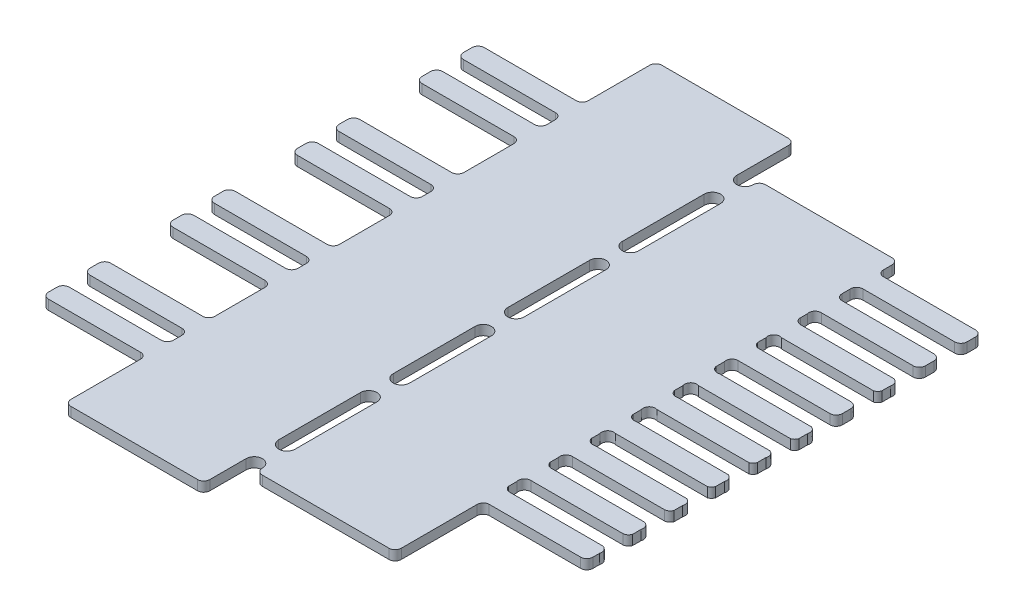
SolidWorks part; units mm, degrees
ref_plane "Front Plane" through (0, 0, 0) normal (0, 0, 1) x (1, 0, 0)
ref_plane "Top Plane" through (0, 0, 0) normal (0, 1, 0) x (1, 0, 0)
ref_plane "Right Plane" through (0, 0, 0) normal (1, 0, 0) x (0, 0, -1)
sketch "Sketch1" plane through (0, 0, 0) normal (0, 1, 0) x (1, 0, 0)
  line L0 (-0.75, 10) -> (-12, 10)
  line L2 (0, 9.25) -> (0, 0.75)
  line L5 (-12.75, 11.27) -> (0, 11.27) construction
  line L7 (-12.75, 10.75) -> (-12.75, 11.79)
  line L8 (-12, 12.54) -> (-0.75, 12.54)
  line L12 (0, 14.33) -> (0, 13.29)
  line L17 (-0.75, 15.08) -> (-12, 15.08)
  line L22 (-12.75, 15.83) -> (-12.75, 16.87)
  line L27 (-12, 17.62) -> (-0.75, 17.62)
  line L56 (16.25, 0) -> (0.75, 0)
  line L84 (0, 19.41) -> (0, 10.91) [skipped]
  line L85 (-0.75, 20.16) -> (-12, 20.16) [skipped]
  line L86 (-12.75, 20.91) -> (-12.75, 21.95) [skipped]
  line L87 (-12, 22.7) -> (-0.75, 22.7) [skipped]
  line L88 (0, 24.49) -> (0, 15.99) [skipped]
  line L89 (-0.75, 25.24) -> (-12, 25.24) [skipped]
  line L90 (-12.75, 25.99) -> (-12.75, 27.03) [skipped]
  line L91 (-12, 27.78) -> (-0.75, 27.78) [skipped]
  line L92 (0, 29.57) -> (0, 21.07) [skipped]
  line L93 (-0.75, 30.32) -> (-12, 30.32) [skipped]
  line L94 (-12.75, 31.07) -> (-12.75, 32.11) [skipped]
  line L95 (-12, 32.86) -> (-0.75, 32.86) [skipped]
  line L96 (0, 34.65) -> (0, 26.15) [skipped]
  line L97 (-0.75, 35.4) -> (-12, 35.4) [skipped]
  line L98 (-12.75, 36.15) -> (-12.75, 37.19) [skipped]
  line L99 (-12, 37.94) -> (-0.75, 37.94) [skipped]
  line L100 (0, 39.73) -> (0, 31.23) [skipped]
  line L101 (-0.75, 40.48) -> (-12, 40.48) [skipped]
  line L102 (-12.75, 41.23) -> (-12.75, 42.27) [skipped]
  line L103 (-12, 43.02) -> (-0.75, 43.02) [skipped]
  line L104 (0, 44.81) -> (0, 36.31) [skipped]
  line L105 (-0.75, 45.56) -> (-12, 45.56) [skipped]
  line L106 (-12.75, 46.31) -> (-12.75, 47.35) [skipped]
  line L107 (-12, 48.1) -> (-0.75, 48.1) [skipped]
  line L108 (0, 49.89) -> (0, 41.39) [skipped]
  line L109 (-0.75, 50.64) -> (-12, 50.64) [skipped]
  line L110 (-12.75, 51.39) -> (-12.75, 52.43) [skipped]
  line L111 (-12, 53.18) -> (-0.75, 53.18) [skipped]
  line L112 (0, 54.97) -> (0, 46.47) [skipped]
  line L113 (-0.75, 55.72) -> (-12, 55.72) [skipped]
  line L114 (-12.75, 56.47) -> (-12.75, 57.51) [skipped]
  line L115 (-12, 58.26) -> (-0.75, 58.26) [skipped]
  line L116 (-0.75, 25.24) -> (-12, 25.24)
  line L117 (-12.75, 25.99) -> (-12.75, 27.03)
  line L118 (-12, 27.78) -> (-0.75, 27.78)
  line L119 (0, 29.57) -> (0, 28.53)
  line L120 (-0.75, 30.32) -> (-12, 30.32)
  line L121 (-12.75, 31.07) -> (-12.75, 32.11)
  line L122 (-12, 32.86) -> (-0.75, 32.86)
  line L123 (-0.75, 40.48) -> (-12, 40.48)
  line L124 (-12.75, 41.23) -> (-12.75, 42.27)
  line L125 (-12, 43.02) -> (-0.75, 43.02)
  line L126 (0, 44.81) -> (0, 43.77)
  line L127 (-0.75, 45.56) -> (-12, 45.56)
  line L128 (-12.75, 46.31) -> (-12.75, 47.35)
  line L129 (-12, 48.1) -> (-0.75, 48.1)
  line L130 (-0.75, 55.72) -> (-12, 55.72)
  line L131 (-12.75, 56.47) -> (-12.75, 57.51)
  line L132 (-12, 58.26) -> (-0.75, 58.26)
  line L133 (0, 60.05) -> (0, 59.01)
  line L134 (-0.75, 60.8) -> (-12, 60.8)
  line L135 (-12.75, 61.55) -> (-12.75, 62.59)
  line L136 (-12, 63.34) -> (-0.75, 63.34)
  line L137 (0, 24.49) -> (0, 18.37)
  line L138 (0, 33.61) -> (0, 39.73)
  line L139 (0, 48.85) -> (0, 54.97)
  line L140 (0, 64.09) -> (0, 71.59)
  line L141 (0.75, 72.34) -> (16.2509, 72.34)
  line L143 (36.75, 63.4781) -> (48.0008, 63.4781)
  line L144 (36, 64.2281) -> (36, 65.2679)
  line L145 (48.75, 62.2081) -> (36, 62.2081) construction
  line L146 (48.7508, 62.7269) -> (48.7492, 61.6893)
  line L147 (47.9992, 60.9405) -> (36.7484, 60.9405)
  line L148 (36, 59.1481) -> (36, 60.1408)
  line L149 (36.75, 58.3981) -> (48.0008, 58.3981)
  line L150 (48.7427, 57.6317) -> (48.7411, 56.6093)
  line L151 (47.9911, 55.8605) -> (36.7403, 55.8605)
  line L152 (36, 54.0681) -> (36, 54.8979)
  line L153 (36.75, 53.3181) -> (48.0008, 53.3181)
  line L154 (48.7343, 52.3417) -> (48.7327, 51.3017)
  line L155 (48.2236, 50.7805) -> (36.9728, 50.7805)
  line L156 (36, 48.7779) -> (36, 49.8179)
  line L157 (36, 14.4742) -> (36, 5.183)
  line L158 (35.25, 4.433) -> (19.75, 4.433)
  line L160 (19.75, 66.0179) -> (35.25, 66.0179)
  line L161 (36.7258, 48.2381) -> (47.9766, 48.2381)
  line L162 (48.7266, 47.4869) -> (48.725, 46.4493)
  line L163 (47.975, 45.7005) -> (36.7242, 45.7005)
  line L164 (36, 43.6979) -> (36, 44.7379)
  line L165 (36.9606, 43.1581) -> (48.2114, 43.1581)
  line L166 (48.7182, 42.1817) -> (48.7166, 41.1418)
  line L167 (48.2075, 40.6205) -> (36.9567, 40.6205)
  line L168 (36, 38.6179) -> (36, 39.6579)
  line L169 (36.9525, 38.0781) -> (48.2034, 38.0781)
  line L170 (48.7102, 37.1018) -> (48.7085, 36.0618)
  line L171 (48.1995, 35.5405) -> (36.9486, 35.5405)
  line L172 (36, 33.5379) -> (36, 34.5779)
  line L173 (36.9445, 32.9981) -> (48.1953, 32.9981)
  line L174 (48.7021, 32.0218) -> (48.7005, 30.9818)
  line L175 (48.1914, 30.4605) -> (36.9406, 30.4605)
  line L176 (36, 28.4579) -> (36, 29.4979)
  line L177 (36.9364, 27.9181) -> (48.1872, 27.9181)
  line L178 (48.6941, 26.9418) -> (48.6924, 25.9018)
  line L179 (48, 25.3805) -> (36.75, 25.3805)
  line L180 (36, 23.3779) -> (36, 24.4179)
  line L181 (36.75, 22.8381) -> (48, 22.8381)
  line L182 (48.686, 21.8618) -> (48.6843, 20.8218)
  line L183 (48, 20.3005) -> (36.75, 20.3005)
  line L184 (36, 18.2979) -> (36, 19.3379)
  line L185 (36.75, 17.7581) -> (48, 17.7581)
  line L186 (48.6779, 16.7818) -> (48.6766, 15.9693)
  line L187 (47.9266, 15.2205) -> (36.6758, 15.2205)
  line L188 (18, 5.183) -> (18, 58.6377) construction
  line L190 (17, 0.75) -> (17, 5.183)
  line L191 (19, 5.183) -> (18, 5.183) construction
  line L192 (19, 65.2679) -> (18, 65.2679) construction
  line L193 (18.5, 59.1377) -> (18.5, 63.2679) construction
  line L194 (17.5, 63.2679) -> (17.5, 59.1377) construction
  line L195 (17, 65.2679) -> (17, 71.6258)
  line L196 (18, 58.6377) -> (18, 59.6377) construction
  line L197 (18, 59.6377) -> (18, 62.7679) construction
  line L198 (18, 62.7679) -> (18, 63.7679) construction
  line L199 (18, 63.7679) -> (18, 65.2679) construction
  line L212 (18, 65.2679) -> (17, 65.2679) construction
  line L213 (18, 65.2679) -> (18, 64.7679) construction
  line L218 (18, 5.183) -> (17, 5.183) construction
  arc A0 (-0.75, 12.54) -> (0, 13.29) centre (-0.75, 13.29) ccw
  arc A1 (-12.75, 11.79) -> (-12, 12.54) centre (-12, 11.79) cw
  arc A2 (-12, 10) -> (-12.75, 10.75) centre (-12, 10.75) cw
  arc A3 (0, 0.75) -> (0.75, 0) centre (0.75, 0.75) ccw
  arc A4 (-0.75, 10) -> (0, 9.25) centre (-0.75, 9.25) cw
  arc A5 (17, 0.75) -> (16.25, 0) centre (16.25, 0.75) cw
  arc A6 (-0.75, 15.08) -> (0, 14.33) centre (-0.75, 14.33) cw
  arc A7 (-12, 15.08) -> (-12.75, 15.83) centre (-12, 15.83) cw
  arc A8 (-12.75, 16.87) -> (-12, 17.62) centre (-12, 16.87) cw
  arc A9 (-0.75, 17.62) -> (0, 18.37) centre (-0.75, 18.37) ccw
  arc A44 (-0.75, 20.16) -> (0, 19.41) centre (-0.75, 19.41) cw [skipped]
  arc A45 (-12, 20.16) -> (-12.75, 20.91) centre (-12, 20.91) cw [skipped]
  arc A46 (-12.75, 21.95) -> (-12, 22.7) centre (-12, 21.95) cw [skipped]
  arc A47 (-0.75, 22.7) -> (0, 23.45) centre (-0.75, 23.45) ccw [skipped]
  arc A48 (-0.75, 25.24) -> (0, 24.49) centre (-0.75, 24.49) cw [skipped]
  arc A49 (-12, 25.24) -> (-12.75, 25.99) centre (-12, 25.99) cw [skipped]
  arc A50 (-12.75, 27.03) -> (-12, 27.78) centre (-12, 27.03) cw [skipped]
  arc A51 (-0.75, 27.78) -> (0, 28.53) centre (-0.75, 28.53) ccw [skipped]
  arc A52 (-0.75, 30.32) -> (0, 29.57) centre (-0.75, 29.57) cw [skipped]
  arc A53 (-12, 30.32) -> (-12.75, 31.07) centre (-12, 31.07) cw [skipped]
  arc A54 (-12.75, 32.11) -> (-12, 32.86) centre (-12, 32.11) cw [skipped]
  arc A55 (-0.75, 32.86) -> (0, 33.61) centre (-0.75, 33.61) ccw [skipped]
  arc A56 (-0.75, 35.4) -> (0, 34.65) centre (-0.75, 34.65) cw [skipped]
  arc A57 (-12, 35.4) -> (-12.75, 36.15) centre (-12, 36.15) cw [skipped]
  arc A58 (-12.75, 37.19) -> (-12, 37.94) centre (-12, 37.19) cw [skipped]
  arc A59 (-0.75, 37.94) -> (0, 38.69) centre (-0.75, 38.69) ccw [skipped]
  arc A60 (-0.75, 40.48) -> (0, 39.73) centre (-0.75, 39.73) cw [skipped]
  arc A61 (-12, 40.48) -> (-12.75, 41.23) centre (-12, 41.23) cw [skipped]
  arc A62 (-12.75, 42.27) -> (-12, 43.02) centre (-12, 42.27) cw [skipped]
  arc A63 (-0.75, 43.02) -> (0, 43.77) centre (-0.75, 43.77) ccw [skipped]
  arc A64 (-0.75, 45.56) -> (0, 44.81) centre (-0.75, 44.81) cw [skipped]
  arc A65 (-12, 45.56) -> (-12.75, 46.31) centre (-12, 46.31) cw [skipped]
  arc A66 (-12.75, 47.35) -> (-12, 48.1) centre (-12, 47.35) cw [skipped]
  arc A67 (-0.75, 48.1) -> (0, 48.85) centre (-0.75, 48.85) ccw [skipped]
  arc A68 (-0.75, 50.64) -> (0, 49.89) centre (-0.75, 49.89) cw [skipped]
  arc A69 (-12, 50.64) -> (-12.75, 51.39) centre (-12, 51.39) cw [skipped]
  arc A70 (-12.75, 52.43) -> (-12, 53.18) centre (-12, 52.43) cw [skipped]
  arc A71 (-0.75, 53.18) -> (0, 53.93) centre (-0.75, 53.93) ccw [skipped]
  arc A72 (-0.75, 55.72) -> (0, 54.97) centre (-0.75, 54.97) cw [skipped]
  arc A73 (-12, 55.72) -> (-12.75, 56.47) centre (-12, 56.47) cw [skipped]
  arc A74 (-12.75, 57.51) -> (-12, 58.26) centre (-12, 57.51) cw [skipped]
  arc A75 (-0.75, 58.26) -> (0, 59.01) centre (-0.75, 59.01) ccw [skipped]
  arc A76 (-0.75, 27.78) -> (0, 28.53) centre (-0.75, 28.53) ccw
  arc A77 (-12.75, 27.03) -> (-12, 27.78) centre (-12, 27.03) cw
  arc A78 (-12, 25.24) -> (-12.75, 25.99) centre (-12, 25.99) cw
  arc A79 (-0.75, 25.24) -> (0, 24.49) centre (-0.75, 24.49) cw
  arc A80 (-0.75, 30.32) -> (0, 29.57) centre (-0.75, 29.57) cw
  arc A81 (-12, 30.32) -> (-12.75, 31.07) centre (-12, 31.07) cw
  arc A82 (-12.75, 32.11) -> (-12, 32.86) centre (-12, 32.11) cw
  arc A83 (-0.75, 32.86) -> (0, 33.61) centre (-0.75, 33.61) ccw
  arc A84 (-0.75, 43.02) -> (0, 43.77) centre (-0.75, 43.77) ccw
  arc A85 (-12.75, 42.27) -> (-12, 43.02) centre (-12, 42.27) cw
  arc A86 (-12, 40.48) -> (-12.75, 41.23) centre (-12, 41.23) cw
  arc A87 (-0.75, 40.48) -> (0, 39.73) centre (-0.75, 39.73) cw
  arc A88 (-0.75, 45.56) -> (0, 44.81) centre (-0.75, 44.81) cw
  arc A89 (-12, 45.56) -> (-12.75, 46.31) centre (-12, 46.31) cw
  arc A90 (-12.75, 47.35) -> (-12, 48.1) centre (-12, 47.35) cw
  arc A91 (-0.75, 48.1) -> (0, 48.85) centre (-0.75, 48.85) ccw
  arc A92 (-0.75, 58.26) -> (0, 59.01) centre (-0.75, 59.01) ccw
  arc A93 (-12.75, 57.51) -> (-12, 58.26) centre (-12, 57.51) cw
  arc A94 (-12, 55.72) -> (-12.75, 56.47) centre (-12, 56.47) cw
  arc A95 (-0.75, 55.72) -> (0, 54.97) centre (-0.75, 54.97) cw
  arc A96 (-0.75, 60.8) -> (0, 60.05) centre (-0.75, 60.05) cw
  arc A97 (-12, 60.8) -> (-12.75, 61.55) centre (-12, 61.55) cw
  arc A98 (-12.75, 62.59) -> (-12, 63.34) centre (-12, 62.59) cw
  arc A99 (-0.75, 63.34) -> (0, 64.09) centre (-0.75, 64.09) ccw
  arc A100 (0, 71.59) -> (0.75, 72.34) centre (0.75, 71.59) cw
  arc A101 (16.2509, 72.34) -> (17, 71.6258) centre (16.2509, 71.59) cw
  arc A102 (36.7484, 60.9405) -> (36, 60.1408) centre (36.7484, 60.1905) ccw
  arc A103 (48.7492, 61.6893) -> (47.9992, 60.9405) centre (47.9992, 61.6905) cw
  arc A104 (48.0008, 63.4781) -> (48.7508, 62.7269) centre (48.0008, 62.7281) cw
  arc A105 (36, 65.2679) -> (35.25, 66.0179) centre (35.25, 65.2679) ccw
  arc A106 (36.75, 63.4781) -> (36, 64.2281) centre (36.75, 64.2281) cw
  arc A107 (19, 65.2679) -> (19.75, 66.0179) centre (19.75, 65.2679) cw
  arc A108 (36.75, 58.3981) -> (36, 59.1481) centre (36.75, 59.1481) cw
  arc A109 (48.0008, 58.3981) -> (48.7427, 57.6317) centre (47.9929, 57.6482) cw
  arc A110 (48.7411, 56.6093) -> (47.9911, 55.8605) centre (47.9911, 56.6105) cw
  arc A111 (36.7403, 55.8605) -> (36, 54.8979) centre (36.7191, 55.1108) ccw
  arc A112 (36.75, 53.3181) -> (36, 54.0681) centre (36.75, 54.0681) cw
  arc A113 (48.0008, 53.3181) -> (48.7343, 52.3417) centre (48.0194, 52.5684) cw
  arc A114 (48.7327, 51.3017) -> (48.2236, 50.7805) centre (48.0092, 51.4992) cw
  arc A115 (36.9728, 50.7805) -> (36, 49.8179) centre (36.7023, 50.081) ccw
  arc A116 (36.7258, 48.2381) -> (36, 48.7779) centre (36.7199, 48.9881) cw
  arc A117 (47.9766, 48.2381) -> (48.7266, 47.4869) centre (47.9766, 47.4881) cw
  arc A118 (48.725, 46.4493) -> (47.975, 45.7005) centre (47.975, 46.4505) cw
  arc A119 (36.7242, 45.7005) -> (36, 44.7379) centre (36.7192, 44.9505) ccw
  arc A120 (36.9606, 43.1581) -> (36, 43.6979) centre (36.7296, 43.8717) cw
  arc A121 (48.2114, 43.1581) -> (48.7182, 42.1817) centre (48.0123, 42.435) cw
  arc A122 (48.7166, 41.1418) -> (48.2075, 40.6205) centre (47.993, 41.3392) cw
  arc A123 (36.9567, 40.6205) -> (36, 39.6579) centre (36.7049, 39.914) ccw
  arc A124 (36.9525, 38.0781) -> (36, 38.6179) centre (36.729, 38.794) cw
  arc A125 (48.2034, 38.0781) -> (48.7102, 37.1018) centre (48.0042, 37.355) cw
  arc A126 (48.7085, 36.0618) -> (48.1995, 35.5405) centre (47.985, 36.2592) cw
  arc A127 (36.9486, 35.5405) -> (36, 34.5779) centre (36.7061, 34.8308) ccw
  arc A128 (36.9445, 32.9981) -> (36, 33.5379) centre (36.7285, 33.7163) cw
  arc A129 (48.1953, 32.9981) -> (48.7021, 32.0218) centre (47.9962, 32.275) cw
  arc A130 (48.7005, 30.9818) -> (48.1914, 30.4605) centre (47.9769, 31.1792) cw
  arc A131 (36.9406, 30.4605) -> (36, 29.4979) centre (36.7071, 29.7478) ccw
  arc A132 (36.9364, 27.9181) -> (36, 28.4579) centre (36.7279, 28.6386) cw
  arc A133 (48.1872, 27.9181) -> (48.6941, 26.9418) centre (47.9881, 27.195) cw
  arc A134 (48.6924, 25.9018) -> (48, 25.3805) centre (47.978, 26.1302) cw
  arc A135 (36.75, 25.3805) -> (36, 24.4179) centre (36.719, 24.6311) ccw
  arc A136 (36.75, 22.8381) -> (36, 23.3779) centre (36.7201, 23.5875) cw
  arc A137 (48, 22.8381) -> (48.686, 21.8618) centre (47.9711, 22.0887) cw
  arc A138 (48.6843, 20.8218) -> (48, 20.3005) centre (47.9699, 21.0499) cw
  arc A139 (36.75, 20.3005) -> (36, 19.3379) centre (36.719, 19.5511) ccw
  arc A140 (36.75, 17.7581) -> (36, 18.2979) centre (36.7201, 18.5075) cw
  arc A141 (48, 17.7581) -> (48.6779, 16.7818) centre (47.9632, 17.009) cw
  arc A142 (48.6766, 15.9693) -> (47.9266, 15.2205) centre (47.9266, 15.9705) cw
  arc A143 (36.6758, 15.2205) -> (36, 14.4742) centre (36.75, 14.4742) ccw
  arc A144 (36, 5.183) -> (35.25, 4.433) centre (35.25, 5.183) cw
  arc A145 (19.75, 4.433) -> (19, 5.183) centre (19.75, 5.183) cw
  arc A147 (19, 5.183) -> (17, 5.183) centre (18, 5.183) ccw
  arc A148 (17, 5.183) -> (19, 5.183) centre (18, 5.183) ccw construction
  arc A149 (18.5, 63.2679) -> (17.5, 63.2679) centre (18, 63.2679) ccw construction
  arc A150 (17.5, 59.1377) -> (18.5, 59.1377) centre (18, 59.1377) ccw construction
  arc A151 (18, 59.6377) -> (17.5, 59.1377) centre (18, 59.1377) ccw construction
  arc A152 (18.5, 59.1377) -> (18, 59.6377) centre (18, 59.1377) ccw construction
  arc A153 (18, 62.7679) -> (18.5, 63.2679) centre (18, 63.2679) ccw construction
  arc A154 (17.5, 63.2679) -> (18, 62.7679) centre (18, 63.2679) ccw construction
  arc A155 (17, 65.2679) -> (19, 65.2679) centre (18, 65.2679) ccw
  arc A156 (19, 65.2679) -> (17, 65.2679) centre (18, 65.2679) ccw construction
  point P0 (0, 0)
  point P27 (36, 66.0181)
  point P48 (-12.75, 12.54)
  point P69 (-12.75, 10)
  point P78 (0, 0)
  point P81 (0, 10)
  point P140 (36, 60.9405)
  dimension "D6" = 0.75
  dimension "D7" = 0.75
  dimension "D8" = 4
  dimension "D9" = 10.16
  dimension "D11" = 0.75
  dimension "D13" = 0.75
  dimension "D14" = 0.75
  dimension "D15" = 0.75
  dimension "D16" = 0.75
  dimension "D12" = 9
  dimension "D21" = 17
  dimension "D22" = 17
  dimension "D5" = 2
  dimension "D24" = 4.1302
  dimension "D25" = 5.08
  dimension "D1" = 2.54
  dimension "D2" = 12
  dimension "D3" = 10
  dimension "D4" = 10
  dimension "D10" = 5.08
  dimension "D17" = 5.08
  dimension "D18" = 12
  dimension "D19" = 5.08
  dimension "D20" = 4.433
  dimension "D23" = 2.5397
  dimension "D26" = 5.08
  dimension "D27" = 5.08
  dimension "D28" = 5.08
  dimension "D29" = 5.08
  dimension "D30" = 5.08
  dimension "D31" = 5.08
  dimension "D32" = 5.08
  dimension "D33" = 5.08
  dimension "D34" = 5.08
  dimension "D35" = 5.08
  dimension "D36" = 5.08
  dimension "D37" = 5.08
  dimension "D38" = 5.08
  dimension "D39" = 5.08
  dimension "D40" = 5.08
  dimension "D41" = 5.08
extrude "Boss-Extrude1" add sketch "Sketch1" along normal blind 1.2
sketch "Sketch2" plane through (0, 0, 0) normal (0, -1, 0) x (1, 0, 0)
  line L0 (18, -5.183) -> (18, -65.2679) construction
  line L1 (18, -61.2679) -> (18, -51.2479) construction
  line L2 (17, -61.2679) -> (17, -51.2479)
  line L3 (19, -61.2679) -> (19, -51.2479)
  line L4 (18, -35.2254) -> (0, -35.2254) construction
  line L5 (0, -39.73) -> (0, -33.61) construction
  line L6 (18, -47.2479) -> (18, -37.2279) construction
  line L7 (17, -47.2479) -> (17, -37.2279)
  line L8 (19, -47.2479) -> (19, -37.2279)
  line L9 (18, -23.203) -> (18, -33.223) construction
  line L10 (17, -23.203) -> (17, -33.223)
  line L11 (19, -23.203) -> (19, -33.223)
  line L12 (18, -9.183) -> (18, -19.203) construction
  line L13 (17, -9.183) -> (17, -19.203)
  line L14 (19, -9.183) -> (19, -19.203)
  arc A0 (17, -61.2679) -> (19, -61.2679) centre (18, -61.2679) ccw
  arc A1 (19, -51.2479) -> (17, -51.2479) centre (18, -51.2479) ccw
  circle A2 centre (18, -65.2679) radius 1 construction
  arc A3 (19, -65.2679) -> (17, -65.2679) centre (18, -65.2679) ccw construction
  arc A4 (17, -47.2479) -> (19, -47.2479) centre (18, -47.2479) ccw
  arc A5 (19, -37.2279) -> (17, -37.2279) centre (18, -37.2279) ccw
  arc A6 (17, -23.203) -> (19, -23.203) centre (18, -23.203) cw
  arc A7 (19, -33.223) -> (17, -33.223) centre (18, -33.223) cw
  arc A8 (17, -9.183) -> (19, -9.183) centre (18, -9.183) cw
  arc A9 (19, -19.203) -> (17, -19.203) centre (18, -19.203) cw
  point P6 (18, -56.2579)
  point P23 (18, -42.2379)
  point P28 (18, -28.213)
  point P35 (18, -14.193)
  dimension "D1" = 10.02
  dimension "D2" = 4
  dimension "D3" = 2
extrude "Cut-Extrude1" cut sketch "Sketch2" against normal through all
equation "\"T\"= 1"
